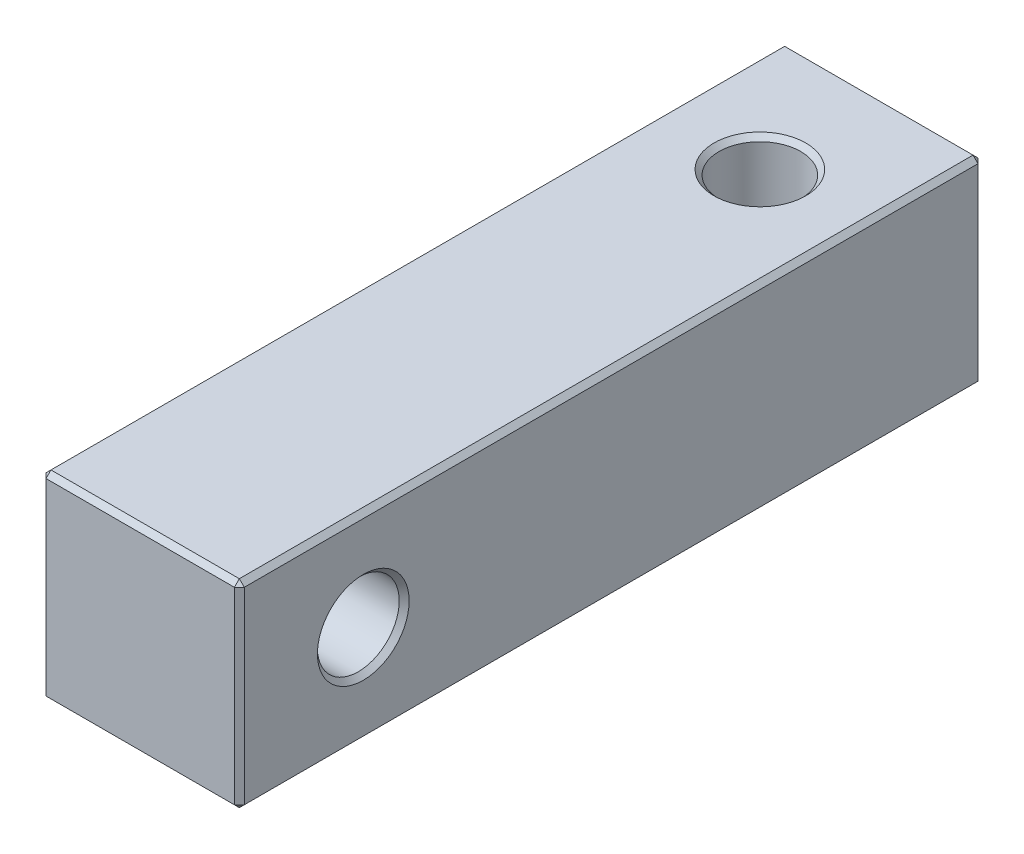
SolidWorks part; units mm, degrees
ref_plane "前视基准面" through (0, 0, 0) normal (0, 0, 1) x (1, 0, 0)
ref_plane "上视基准面" through (0, 0, 0) normal (0, 1, 0) x (1, 0, 0)
ref_plane "右视基准面" through (0, 0, 0) normal (1, 0, 0) x (0, 0, -1)
sketch "草图1" plane through (0, 0, 0) normal (0, 0, 1) x (1, 0, 0)
  line L1 (-4, 4) -> (4, 4)
  line L2 (-4, 4) -> (-4, -4)
  line L3 (-4, -4) -> (4, -4)
  line L4 (4, 4) -> (4, -4)
  line L5 (-4, 4) -> (4, -4) construction
  line L6 (-4, -4) -> (4, 4) construction
  point P0 (0, 0)
  dimension "D1" = 8
extrude "凸台-拉伸1" add sketch "草图1" along normal mid plane 30
hole_wizard "M4 螺纹孔1" positions "草图2" profile "草图3" tap size "M4" standard "GB" end condition through all
sketch "草图2" plane through (4, 0, 0) normal (1, 0, 0) x (0, 0, -1)
  line L0 (0, 0) -> (50000, 0) construction
  line L1 (15, -4) -> (15, 4) construction
  point P0 (-10, 0)
  point P7 (0, 0)
  dimension "D1" = 25
sketch "草图3" plane through (4, 0, 10) normal (0, 1, 0) x (0, 0, -1)
  line L0 (0, 0) -> (0, 8)
  line L1 (0, 8) -> (1.65, 8)
  line L2 (1.65, 8) -> (1.65, 0)
  line L5 (1.65, 0) -> (0, 0)
  line L11 (0, -6.35) -> (0, 107.95) construction
  dimension "通孔螺纹孔钻头直径" = 3.3
  dimension "通孔螺纹孔钻头深度" = 8
cosmetic thread "孔螺蚊线1" parameters "D2"=4
hole_wizard "M4 螺纹孔2" positions "草图4" profile "草图5" tap size "M4" standard "GB" end condition through all
sketch "草图4" plane through (0, 4, 0) normal (0, 1, 0) x (1, 0, 0)
  line L0 (4, -15) -> (-4, -15) construction
  line L1 (0, 0) -> (0, 50000) construction
  point P0 (0, 10)
  point P8 (0, 0)
  dimension "D1" = 25
sketch "草图5" plane through (0, 4, -10) normal (1, 0, 0) x (0, 0, 1)
  line L0 (0, 0) -> (0, 8)
  line L1 (0, 8) -> (1.65, 8)
  line L2 (1.65, 8) -> (1.65, 0)
  line L5 (1.65, 0) -> (0, 0)
  line L11 (0, -6.35) -> (0, 107.95) construction
  dimension "通孔螺纹孔钻头直径" = 3.3
  dimension "通孔螺纹孔钻头深度" = 8
cosmetic thread "孔螺蚊线2" parameters "D2"=4
chamfer "倒角1" distance 0.2 angle 45 16 edges at (0, -4, -8.35) (-4, 0, 8.35) (0, 4, -8.35) (0, -4, 15) (0, -4, -15) (-4, 0, 15) (-4, -4, 0) (-4, 0, -15) (0, 4, 15) (-4, 4, 0) (0, 4, -15) (4, -4, 0) (4, 0, 15) (4, 4, 0) (4, 0, -15) (4, 0, 8.35)
